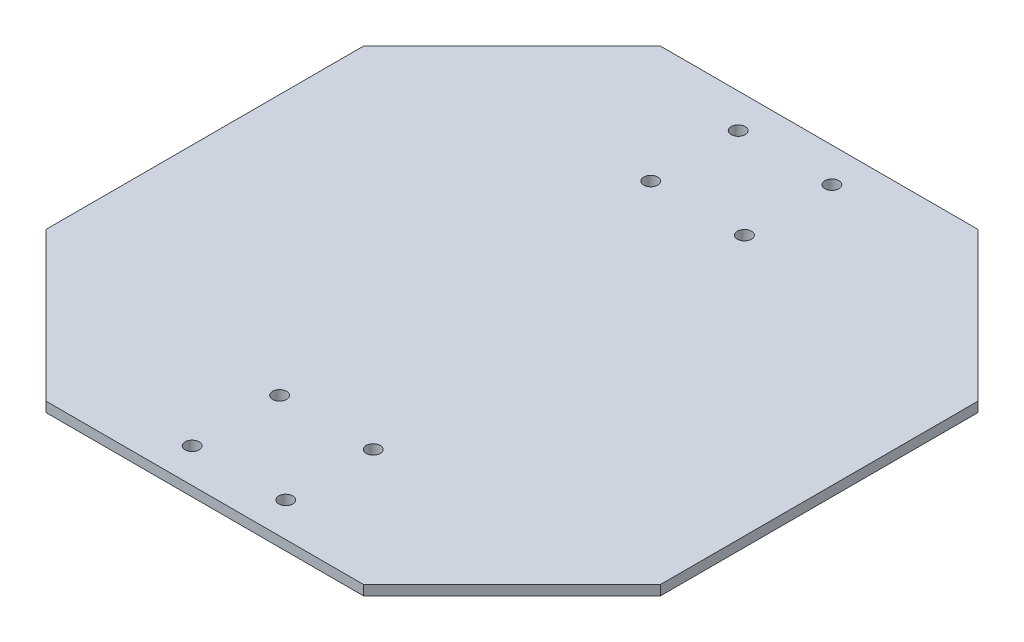
SolidWorks part; units mm, degrees
material "Balsa"
ref_plane "Front Plane" through (0, 0, 0) normal (0, 0, 1) x (1, 0, 0)
ref_plane "Top Plane" through (0, 0, 0) normal (0, 1, 0) x (1, 0, 0)
ref_plane "Right Plane" through (0, 0, 0) normal (1, 0, 0) x (0, 0, -1)
sketch "Sketch1" plane through (0, 0, 0) normal (0, 1, 0) x (1, 0, 0)
  line L0 (-98.425, 50.8) -> (-50.8, 98.425)
  line L1 (-50.8, 98.425) -> (50.8, 98.425)
  line L2 (-98.425, 50.8) -> (-98.425, -50.8)
  line L3 (-50.8, -98.425) -> (50.8, -98.425)
  line L4 (98.425, 50.8) -> (98.425, -50.8)
  line L7 (-98.425, -50.8) -> (-50.8, -98.425)
  line L8 (50.8, 98.425) -> (98.425, 50.8)
  line L9 (50.8, -98.425) -> (98.425, -50.8)
  point P0 (0, 0)
  point P1 (0, 98.425)
  point P2 (-98.425, 0)
  point P3 (-105.3929, 50.8)
  point P4 (0, 0)
  dimension "D1" = 101.6
  dimension "D2" = 196.85
  dimension "D3" = 196.85
extrude "Boss-Extrude1" add sketch "Sketch1" along normal blind 3.175
sketch "Sketch2" plane through (0, 3.175, 0) normal (0, 1, 0) x (1, 0, 0)
  line L0 (50.8, 98.425) -> (-50.8, 98.425) construction
  line L1 (-15, 87.425) -> (15, 87.425) construction
  line L2 (-15, 87.425) -> (-15, 59.425) construction
  line L3 (-15, 59.425) -> (15, 59.425) construction
  line L4 (15, 87.425) -> (15, 59.425) construction
  line L5 (-15, 87.425) -> (15, 59.425) construction
  line L6 (-15, 59.425) -> (15, 87.425) construction
  point P0 (0, 73.425)
  dimension "D1" = 28
  dimension "D2" = 11
  dimension "D3" = 30
hole_wizard "M4 Clearance Hole1" positions "3DSketch1" profile "Sketch3" hole size "M4" standard "ANSI Metric" end condition through all
sketch3d "3DSketch1"
  point P0 (-15, 3.175, -87.425)
  point P3 (-15, 3.175, -59.425)
  point P6 (15, 3.175, -59.425)
  point P9 (15, 3.175, -87.425)
sketch "Sketch3" plane through (-15, 3.175, -87.425) normal (1, 0, 0) x (0, 0, 1)
  line L0 (0, 0) -> (0, 3.175)
  line L1 (0, 3.175) -> (2.25, 3.175)
  line L2 (2.25, 3.175) -> (2.25, 0)
  line L5 (2.25, 0) -> (0, 0)
  line L11 (0, -6.35) -> (0, 107.95) construction
  dimension "Thru Hole Dia." = 4.5
  dimension "Thru Hole Depth" = 3.175
mirror "Mirror1" about plane through (0, 0, 0) normal (0, 0, 1) of "M4 Clearance Hole1"
